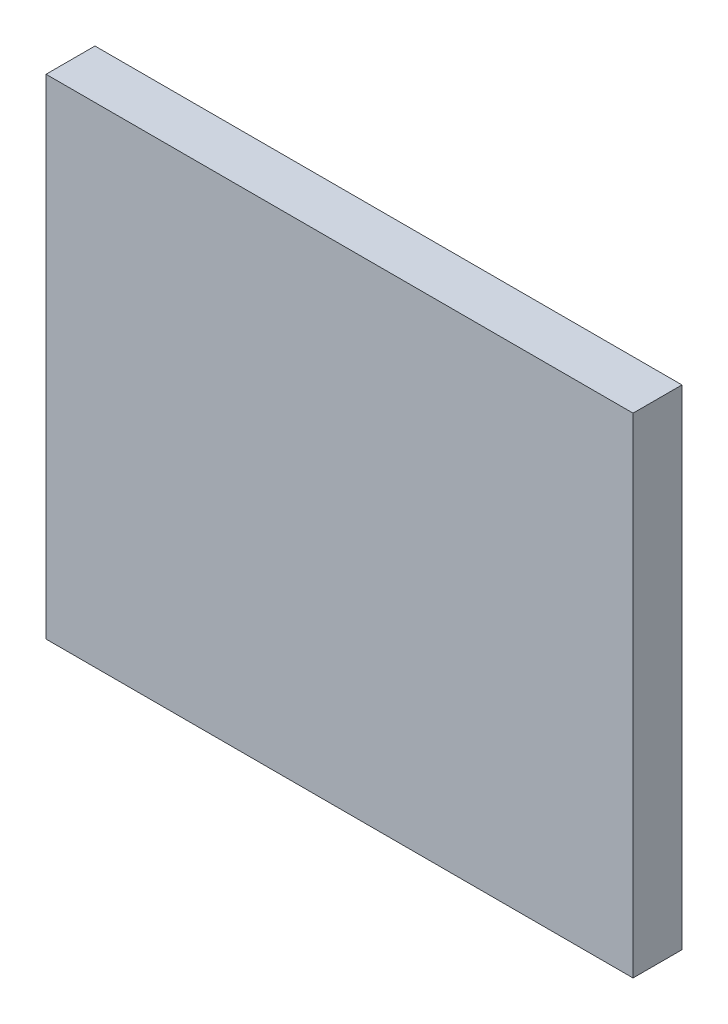
SolidWorks part; units mm, degrees
ref_plane "Front Plane" through (0, 0, 0) normal (0, 0, 1) x (1, 0, 0)
ref_plane "Top Plane" through (0, 0, 0) normal (0, 1, 0) x (1, 0, 0)
ref_plane "Right Plane" through (0, 0, 0) normal (1, 0, 0) x (0, 0, -1)
sketch "Sketch1" plane through (0, 0, 0) normal (0, 0, 1) x (1, 0, 0)
  line L1 (-30, 25) -> (30, 25)
  line L2 (-30, 25) -> (-30, -25)
  line L3 (-30, -25) -> (30, -25)
  line L4 (30, 25) -> (30, -25)
  dimension "D1" = 60
  dimension "D2" = 50
  dimension "D3" = 25
  dimension "D4" = 30
extrude "Boss-Extrude1" add sketch "Sketch1" along normal blind 5
